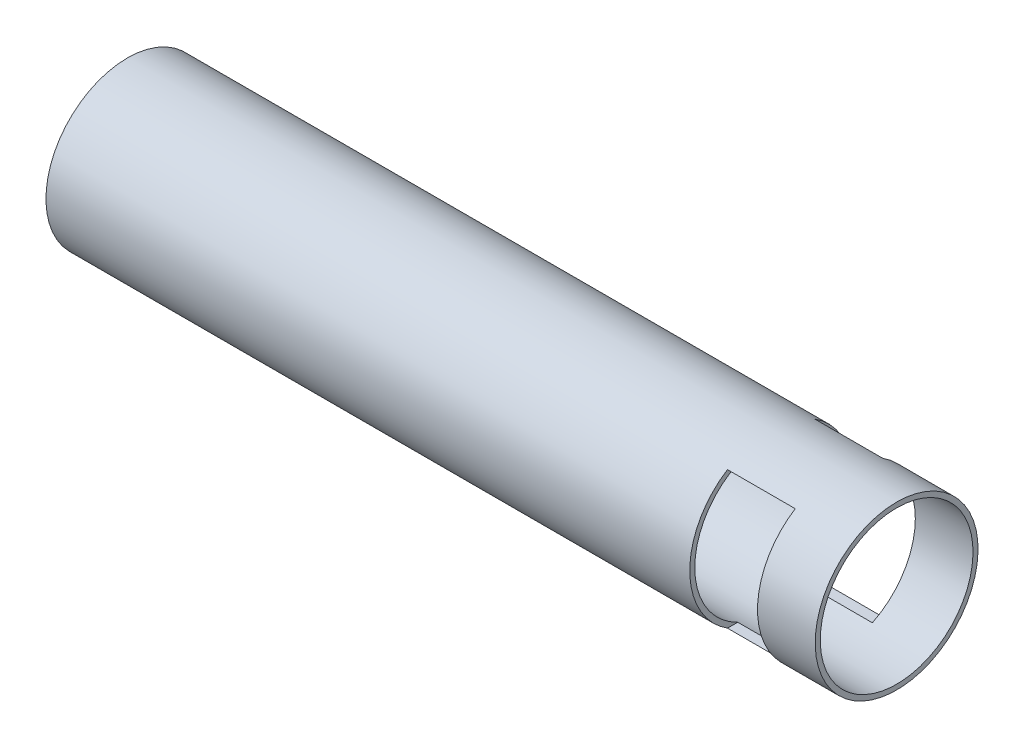
SolidWorks part; units mm, degrees
ref_plane "Front Plane" through (0, 0, 0) normal (0, 0, 1) x (1, 0, 0)
ref_plane "Top Plane" through (0, 0, 0) normal (0, 1, 0) x (1, 0, 0)
ref_plane "Right Plane" through (0, 0, 0) normal (1, 0, 0) x (0, 0, -1)
sketch "Sketch1" plane through (0, 0, 0) normal (0, 0, 1) x (1, 0, 0)
  line L0 (-210, 0) -> (210, 0)
  point P4 (0, 0)
  dimension "D1" = 420
ref_plane "Plane1" through (-210, 0, 0) normal (1, 0, 0) x (0, 1, 0)
other "Pipe 0.5 SCH 40(1)"
ref_plane "Plane2" through (-210, 0, 0) normal (1, 0, 0) x (0, 1, 0)
sketch "Sketch12" plane through (-210, 0, 0) normal (1, 0, 0) x (0, 1, 0)
  circle A0 centre (0, 0) radius 44.45
  circle A1 centre (0, 0) radius 41.7068
  point P0 (0, 0)
  dimension "D1" = 88.9
  dimension "D2" = 83.4136
sketch "Sketch13" plane through (0, 0, 0) normal (0, 0, 1) x (1, 0, 0)
  line L0 (210, 0) -> (160, 0) construction
  line L1 (-210, 0) -> (210, 0) construction
  line L3 (141.5, 37.5) -> (178.5, 37.5)
  line L4 (141.5, 37.5) -> (141.5, -37.5)
  line L5 (141.5, -37.5) -> (178.5, -37.5)
  line L6 (178.5, 37.5) -> (178.5, -37.5)
  line L7 (141.5, 37.5) -> (178.5, -37.5) construction
  line L8 (141.5, -37.5) -> (178.5, 37.5) construction
  dimension "D1" = 37
  dimension "D2" = 75
extrude "Cut-Extrude1" cut sketch "Sketch13" against normal blind 50 and the other way blind 50
